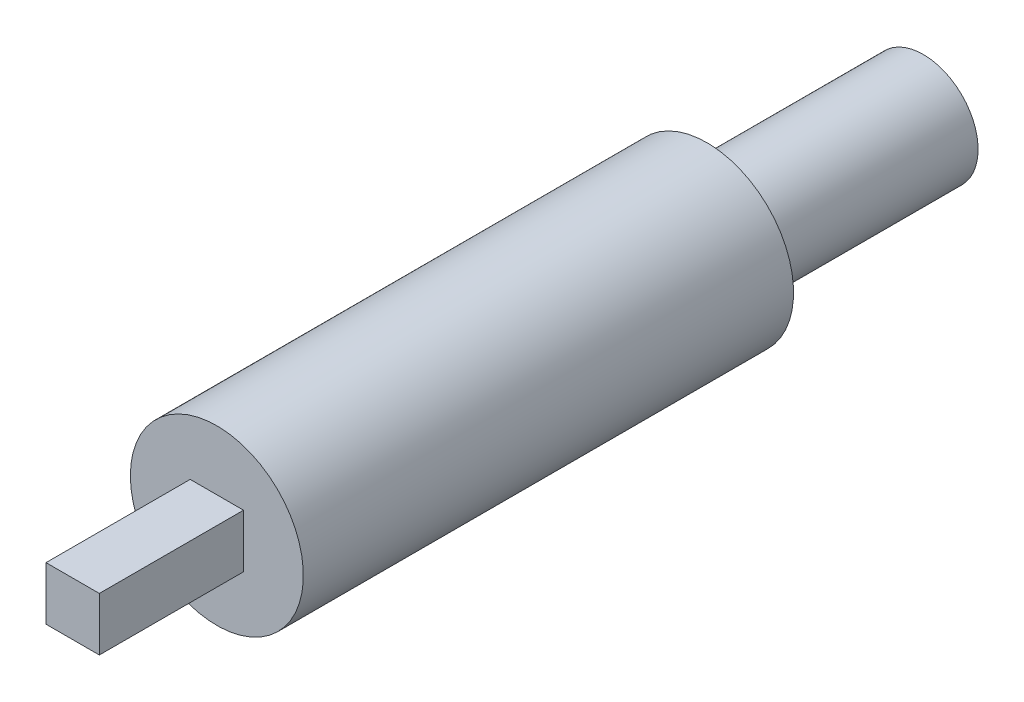
SolidWorks part; units mm, degrees
ref_plane "前视基准面" through (0, 0, 0) normal (0, 0, 1) x (1, 0, 0)
ref_plane "上视基准面" through (0, 0, 0) normal (0, 1, 0) x (1, 0, 0)
ref_plane "右视基准面" through (0, 0, 0) normal (1, 0, 0) x (0, 0, -1)
sketch "Sketch1" plane through (0, 0, 0) normal (0, 0, 1) x (1, 0, 0)
  line L1 (-1.85, 1.85) -> (1.85, 1.85)
  line L2 (-1.85, 1.85) -> (-1.85, -1.85)
  line L3 (-1.85, -1.85) -> (1.85, -1.85)
  line L4 (1.85, 1.85) -> (1.85, -1.85)
  line L5 (-1.85, 1.85) -> (1.85, -1.85) construction
  line L6 (-1.85, -1.85) -> (1.85, 1.85) construction
  point P0 (0, 0)
  dimension "D1" = 3.7
  dimension "D2" = 3.7
extrude "Extrude1" add sketch "Sketch1" along normal blind 10
sketch "Sketch2" plane through (0, 0, 0) normal (0, 0, -1) x (-1, 0, 0)
  circle A0 centre (0, 0) radius 6
  dimension "D1" = 12
extrude "Extrude2" add sketch "Sketch2" along normal blind 34
sketch "Sketch3" plane through (0, 0, -34) normal (0, 0, -1) x (-1, 0, 0)
  circle A0 centre (0, 0) radius 3.8
  dimension "D1" = 7.6
extrude "Extrude3" add sketch "Sketch3" along normal blind 15
